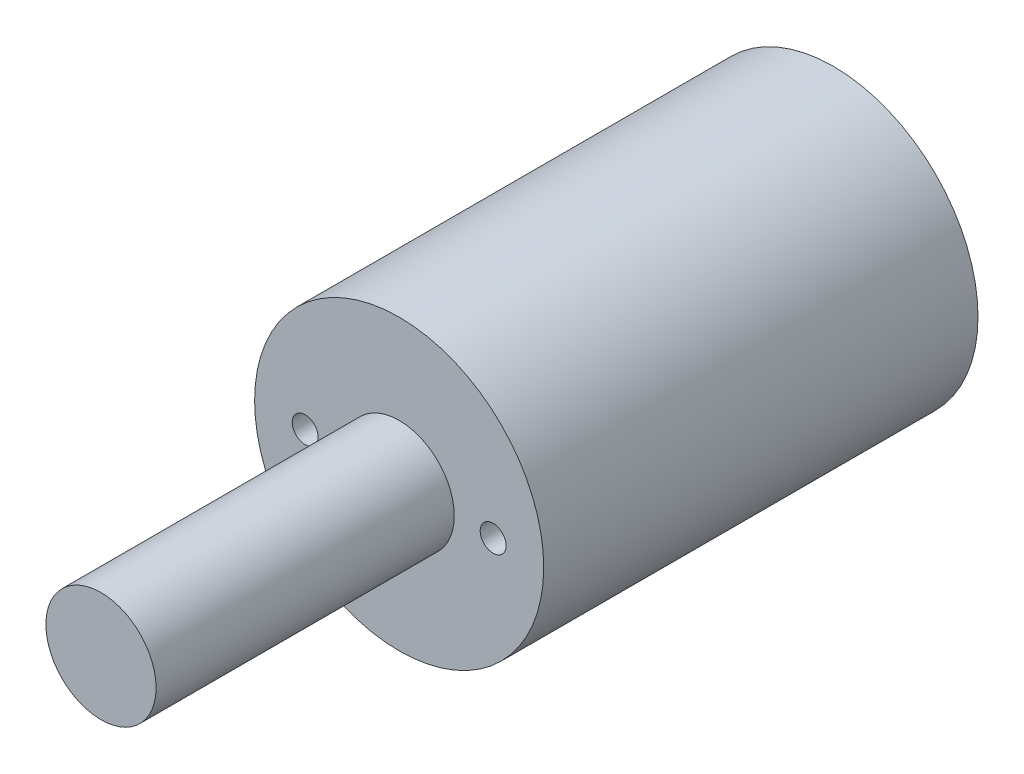
SolidWorks part; units mm, degrees
ref_plane "前基準面" through (0, 0, 0) normal (0, 0, 1) x (1, 0, 0)
ref_plane "上基準面" through (0, 0, 0) normal (0, 1, 0) x (1, 0, 0)
ref_plane "右基準面" through (0, 0, 0) normal (1, 0, 0) x (0, 0, -1)
sketch "草圖1" plane through (0, 0, 0) normal (0, 0, 1) x (1, 0, 0)
  circle A0 centre (0, 0) radius 22.3
  dimension "D1" = 44.6
extrude "填料-伸長1" add sketch "草圖1" along normal blind 67
sketch "草圖2" plane through (0, 0, 67) normal (0, 0, 1) x (1, 0, 0)
  circle A0 centre (0, 0) radius 8.5
  dimension "D1" = 17
extrude "填料-伸長2" add sketch "草圖2" along normal blind 46
sketch "草圖3" plane through (0, 0, 0) normal (0, 0, -1) x (-1, 0, 0)
  circle A0 centre (0, 0) radius 2.5
  dimension "D1" = 5
extrude "填料-伸長3" add sketch "草圖3" along normal blind 7
sketch "草圖4" plane through (0, 0, 67) normal (0, 0, 1) x (1, 0, 0)
  line L0 (0, 8.5) -> (0, -8.5) construction
  circle A0 centre (14.5, 0) radius 2
  circle A1 centre (0, 0) radius 8.5 construction
  circle A2 centre (0, 0) radius 8.5 construction
  circle A3 centre (-14.5, 0) radius 2
  dimension "D1" = 4
  dimension "D2" = 14.5
extrude "除料-伸長1" cut sketch "草圖4" against normal blind 10
